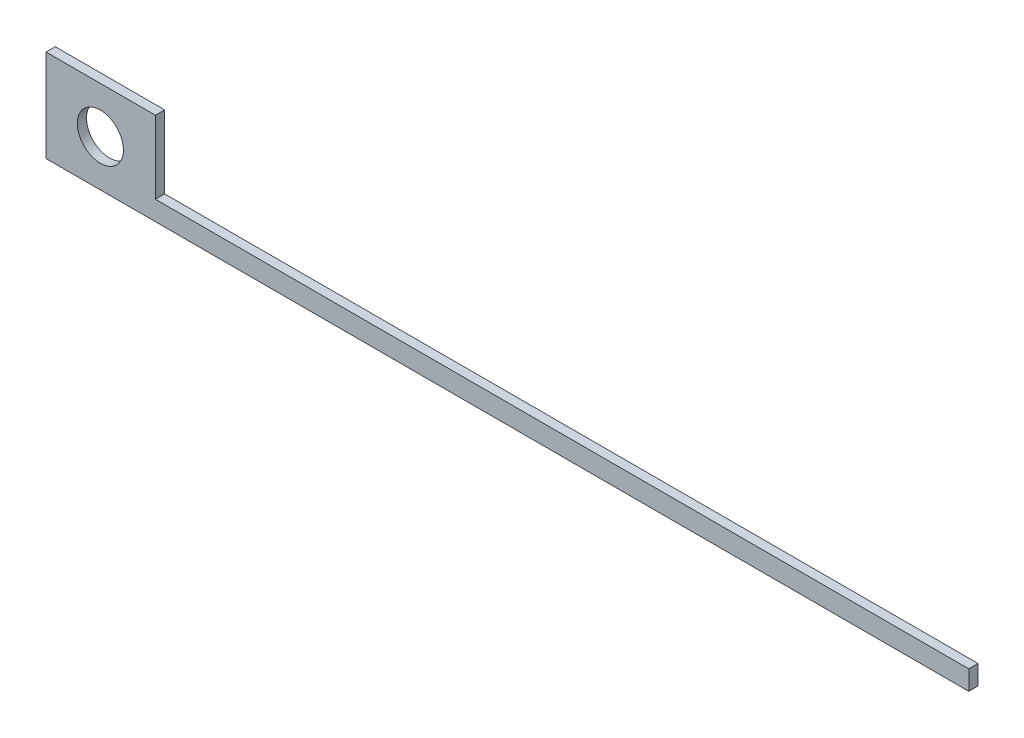
SolidWorks part; units mm, degrees
ref_plane "Front Plane" through (0, 0, 0) normal (0, 0, 1) x (1, 0, 0)
ref_plane "Top Plane" through (0, 0, 0) normal (0, 1, 0) x (1, 0, 0)
ref_plane "Right Plane" through (0, 0, 0) normal (1, 0, 0) x (0, 0, -1)
sketch "Sketch1" plane through (0, 0, 0) normal (0, 0, 1) x (1, 0, 0)
  line L1 (-500, -50) -> (500, -50)
  line L2 (-500, -50) -> (-500, 50)
  line L3 (-500, 50) -> (500, 50)
  line L4 (500, -50) -> (500, 50)
  line L5 (-500, -50) -> (500, 50) construction
  line L6 (-500, 50) -> (500, -50) construction
  point P0 (0, 0)
  dimension "D1" = 1000
  dimension "D2" = 100
extrude "Boss-Extrude1" add sketch "Sketch1" along normal blind 10
sketch "Sketch2" plane through (0, 0, 10) normal (0, 0, 1) x (1, 0, 0)
  circle A0 centre (-441.1099, 0) radius 25
  dimension "D1" = 50
extrude "Cut-Extrude1" cut sketch "Sketch2" against normal blind 10
sketch "Sketch3" plane through (0, 0, 10) normal (0, 0, 1) x (1, 0, 0)
  line L0 (500, 50) -> (-500, 50) construction
  line L1 (-381.3962, 50) -> (500, 50)
  line L2 (-381.3962, 50) -> (-381.3962, -28.8706)
  line L3 (-381.3962, -28.8706) -> (500, -28.8706)
  line L4 (500, 50) -> (500, -28.8706)
  line L5 (500, -50) -> (500, 50) construction
extrude "Cut-Extrude2" cut sketch "Sketch3" against normal blind 10
